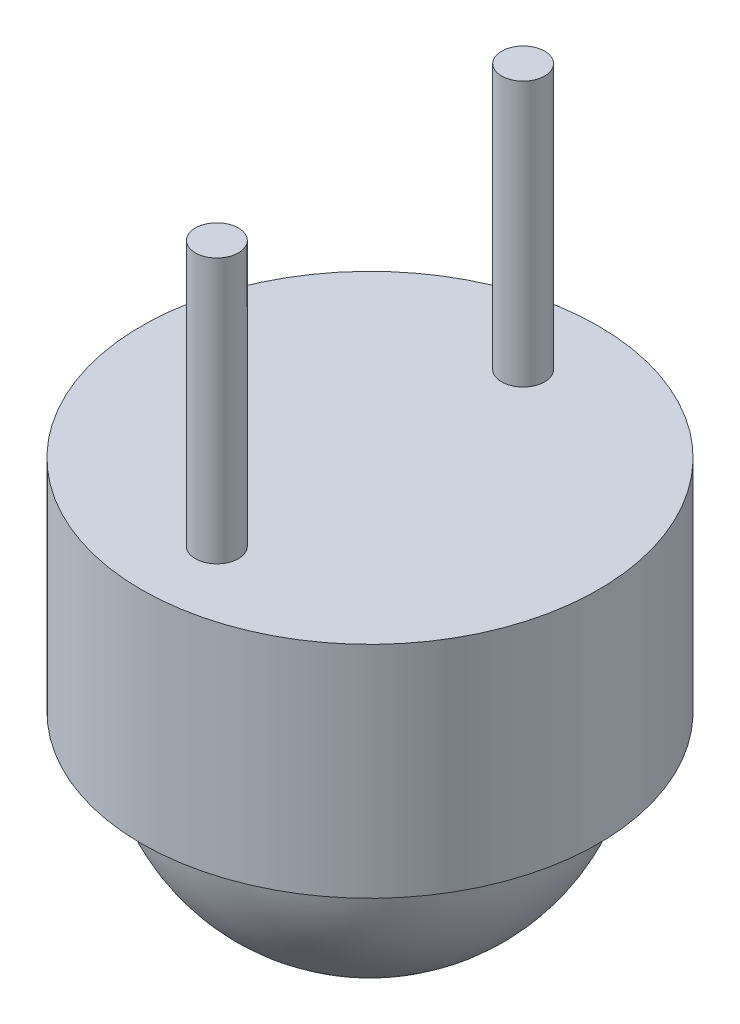
SolidWorks part; units mm, degrees
ref_plane "Front Plane" through (0, 0, 0) normal (0, 0, 1) x (1, 0, 0)
ref_plane "Top Plane" through (0, 0, 0) normal (0, 1, 0) x (1, 0, 0)
ref_plane "Right Plane" through (0, 0, 0) normal (1, 0, 0) x (0, 0, -1)
sketch "Sketch1" plane through (0, 0, 0) normal (0, 0, 1) x (1, 0, 0)
  line L0 (0, -9.525) -> (0, 9.525)
  arc A0 (0, -9.525) -> (0, 9.525) centre (0, 0) ccw
  dimension "D1" = 19.05
revolve "Metal Ball 3/4\"" add sketch "Sketch1" angle 360 about L0
sketch "Sketch2" plane through (0, 0, 0) normal (0, 1, 0) x (1, 0, 0)
  circle A0 centre (0, 0) radius 9.525
  circle A1 centre (0, 0) radius 11.557
  dimension "D1" = 2.032
extrude "Housing Pt. 1" add sketch "Sketch2" along normal blind 9.525 separate body
sketch "Sketch3" plane through (0, 9.525, 0) normal (0, 1, 0) x (1, 0, 0)
  circle A0 centre (0, 0) radius 11.557
  dimension "D1" = 23.114
extrude "Housing Pt. 2" add sketch "Sketch3" along normal blind 1.6
sketch "Sketch4" plane through (0, 11.125, 0) normal (0, 1, 0) x (1, 0, 0)
  line L0 (0, -7.747) -> (0, 7.747) construction
  circle A0 centre (0, 7.747) radius 1.09
  circle A1 centre (0, -7.747) radius 1.09
  point P5 (0, 0)
  dimension "D2" = 2.18
  dimension "D1" = 15.494
extrude "Screw Holes" cut sketch "Sketch4" against normal up to next (1.6 mm away)
sketch "Sketch5" plane through (0, 9.525, 0) normal (0, -1, 0) x (1, 0, 0)
  circle A0 centre (0, 7.747) radius 1.09
  circle A1 centre (0, -7.747) radius 1.09
  dimension "D1" = 2.18
extrude "Screws" add sketch "Sketch5" against normal blind 15 separate body
